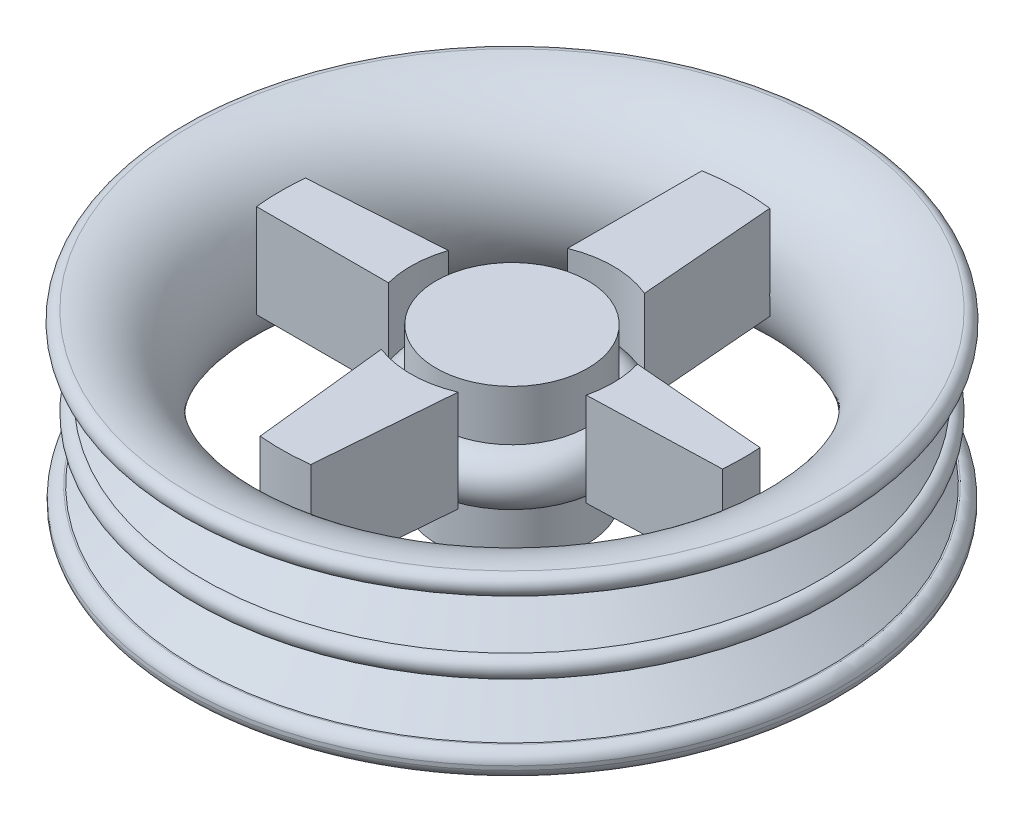
SolidWorks part; units mm, degrees
ref_plane "Front Plane" through (0, 0, 0) normal (0, 0, 1) x (1, 0, 0)
ref_plane "Top Plane" through (0, 0, 0) normal (0, 1, 0) x (1, 0, 0)
ref_plane "Right Plane" through (0, 0, 0) normal (1, 0, 0) x (0, 0, -1)
sketch "Sketch1" plane through (0, 0, 0) normal (0, 0, 1) x (1, 0, 0)
  line L0 (0, 0) -> (0, 60)
  line L1 (0, 60) -> (30, 60)
  line L2 (30, 60) -> (30, 40)
  line L3 (30, 0) -> (0, 0)
  line L4 (30, 20) -> (30, 0)
  line L6 (124.8346, 4.9179) -> (125.3944, 4.9179)
  line L10 (130, 0.7609) -> (130, -0.805)
  line L11 (126.4589, 57.2268) -> (109.1756, 46.215)
  line L12 (109.1756, 46.215) -> (122.4589, 34)
  line L13 (109.1756, 17.277) -> (122.4589, 26)
  line L14 (109.1756, 17.277) -> (124.8346, 4.9179)
  arc A0 (30, 20) -> (30, 40) centre (30, 30) ccw
  arc A1 (126.4589, 65) -> (130, -4.8204) centre (126.4589, 30) ccw
  arc A2 (126.4589, 57.2268) -> (126.4589, 65) centre (126.4589, 61.1134) ccw
  arc A3 (124.8931, -4.965) -> (124.8346, 4.9179) centre (125.1145, -0.022) ccw
  arc A5 (122.4589, 26) -> (122.4589, 34) centre (122.4589, 30) ccw
  dimension "D1" = 10
  dimension "D2" = 35
  dimension "D6" = 8
  dimension "D3" = 30
  dimension "D4" = 130
  dimension "D5" = 30
revolve "Revolve4" add sketch "Sketch1" angle 360 about L0
sketch "Sketch2" plane through (0, 60, 0) normal (0, 1, 0) x (1, 0, 0)
  line L0 (-15.0791, 90.2073) -> (-15.0791, 37.0489)
  line L2 (11.1975, 90.7709) -> (15.5278, 36.8631)
  arc A0 (15.5278, 36.8631) -> (-15.0791, 37.0489) centre (0, 0) ccw
  arc A1 (11.1975, 90.7709) -> (-15.0791, 90.2073) centre (0, 0) ccw
extrude "Boss-Extrude1" add sketch "Sketch2" against normal blind 37 separate body contours L0 A0 L2 A1
sketch "Sketch3" plane through (0, 60, 0) normal (0, 1, 0) x (1, 0, 0)
  line L2 (-14.3411, -37.3408) -> (-8.5448, -91.0589)
  line L3 (15.5278, -36.8631) -> (11.1882, -90.772)
  circle A1 centre (0, 0) radius 40 construction
  circle A2 centre (0, 0) radius 91.4589 construction
  arc A3 (-14.3411, -37.3408) -> (15.5278, -36.8631) centre (0, 0) ccw
  arc A4 (-8.5448, -91.0589) -> (11.1882, -90.772) centre (0, 0) ccw
extrude "Boss-Extrude2" add sketch "Sketch3" against normal blind 37 and the other way blind 3 separate body contours L2 A4 L3 A3
sketch "Sketch4" plane through (0, 60, 0) normal (0, 1, 0) x (1, 0, 0)
  line L0 (38.8509, -9.519) -> (91.1182, -7.8872)
  line L1 (38.4363, 11.0749) -> (38.3931, 11.2235)
  line L2 (38.3931, 11.2235) -> (91.2002, 6.8738)
  circle A0 centre (0, 0) radius 40 construction
  circle A1 centre (0, 0) radius 91.4589 construction
  arc A2 (38.8509, -9.519) -> (38.3931, 11.2235) centre (0, 0) ccw
  arc A3 (91.1182, -7.8872) -> (91.2002, 6.8738) centre (0, 0) ccw
extrude "Boss-Extrude3" add sketch "Sketch4" against normal blind 37 separate body contours A2 L0 A3 L2
sketch "Sketch5" plane through (0, 60, 0) normal (0, 1, 0) x (1, 0, 0)
  line L0 (-90.9832, 9.3164) -> (-37.9079, 12.7669)
  line L1 (-90.8947, -10.1436) -> (-38.6925, -10.1436)
  circle A0 centre (0, 0) radius 91.4589 construction
  circle A1 centre (0, 0) radius 40 construction
  arc A2 (-90.9832, 9.3164) -> (-90.8947, -10.1436) centre (0, 0) ccw
  arc A3 (-37.9079, 12.7669) -> (-38.6925, -10.1436) centre (0, 0) ccw
extrude "Boss-Extrude4" add sketch "Sketch5" against normal blind 37 separate body contours L1 A3 L0 A2
